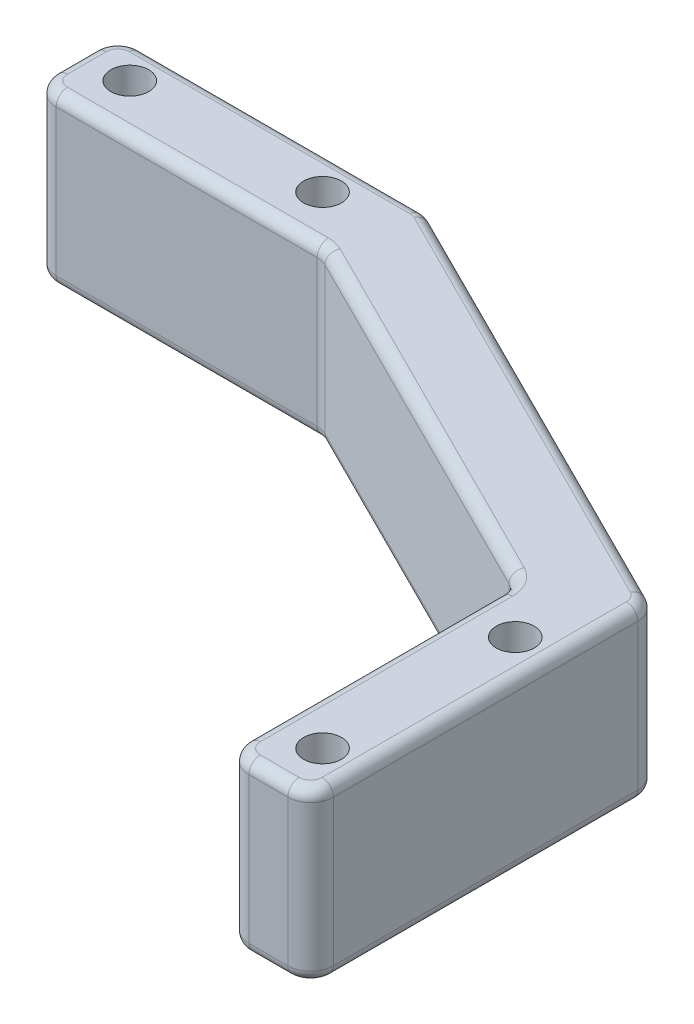
SolidWorks part; units mm, degrees
ref_plane "Front Plane" through (0, 0, 0) normal (0, 0, 1) x (1, 0, 0)
ref_plane "Top Plane" through (0, 0, 0) normal (0, 1, 0) x (1, 0, 0)
ref_plane "Right Plane" through (0, 0, 0) normal (1, 0, 0) x (0, 0, -1)
sketch "Sketch1" plane through (0, 0, 0) normal (0, 1, 0) x (1, 0, 0)
  line L0 (38.1, -11.1252) -> (88.9, -36.5252)
  line L1 (0, 0) -> (38.1, 0)
  line L2 (0, 0) -> (0, -11.1252)
  line L3 (0, -11.1252) -> (38.1, -11.1252)
  line L4 (38.1, 0) -> (38.1, -11.1252)
  line L5 (100.0252, -36.5252) -> (88.9, -36.5252)
  line L6 (100.0252, -36.5252) -> (100.0252, -74.6252)
  line L7 (100.0252, -74.6252) -> (88.9, -74.6252)
  line L8 (88.9, -36.5252) -> (88.9, -74.6252)
  line L9 (38.1, 0) -> (40.7263, 0)
  line L10 (40.7263, 0) -> (100.0252, -29.6494)
  line L11 (100.0252, -29.6494) -> (100.0252, -36.5252)
  circle A0 centre (31.75, -4.7752) radius 2.5
  circle A1 centre (6.35, -4.7752) radius 2.5
  circle A2 centre (95.25, -42.8752) radius 2.5
  circle A3 centre (95.25, -68.2752) radius 2.5
  dimension "D7" = 5
  dimension "D1" = 11.1252
  dimension "D2" = 38.1
  dimension "D3" = 38.1
  dimension "D4" = 11.1252
  dimension "D5" = 6.35
  dimension "D6" = 6.35
  dimension "D8" = 6.35
  dimension "D9" = 6.35
  dimension "D10" = 6.35
  dimension "D11" = 6.35
  dimension "D12" = 38.1
  dimension "D13" = 63.5
  dimension "D14" = 11.1252
extrude "Boss-Extrude1" add sketch "Sketch1" along normal blind 22.2504 contours L4 L1 L2 L3 A1 A0 | L11 L10 L9 L4 L0 L5 | L5 L8 L7 L6 A3 A2
fillet "Fillet1" radius 3 8 edges at (40.7263, 11.1252, 0) (100.0252, 11.1252, 29.6494) (100.0252, 11.1252, 74.6252) (88.9, 11.1252, 74.6252) (38.1, 11.1252, 11.1252) (88.9, 11.1252, 36.5252) (0, 11.1252, 11.1252) (0, 11.1252, 0)
fillet "Fillet2" radius 1.5 32 edges at (0.8787, 22.2504, 10.2465) (0.8787, 0, 10.2465) (0, 0, 5.5626) (0, 22.2504, 5.5626) (0.8787, 22.2504, 0.8787) (0.8787, 0, 0.8787) (21.509, 22.2504, 0) (21.509, 0, 0) (40.7074, 22.2504, 0.0803) (40.7074, 0, 0.0803) (69.8633, 0, 14.5685) (69.8633, 22.2504, 14.5685) (99.5772, 22.2504, 29.9264) (99.5772, 0, 29.9264) (100.0252, 0, 51.5644) (100.0252, 22.2504, 51.5644) (99.1465, 22.2504, 73.7465) (99.1465, 0, 73.7465) (94.4626, 0, 74.6252) (94.4626, 22.2504, 74.6252) (89.7787, 22.2504, 73.7465) (89.7787, 0, 73.7465) (88.9, 0, 55.0023) (88.9, 22.2504, 55.0023) (88.452, 22.2504, 36.8021) (88.452, 0, 36.8021) (62.9875, 22.2504, 23.569) (62.9875, 0, 23.569) (38.0811, 22.2504, 11.2055) (38.0811, 0, 11.2055) (20.1959, 0, 11.1252) (20.1959, 22.2504, 11.1252)
